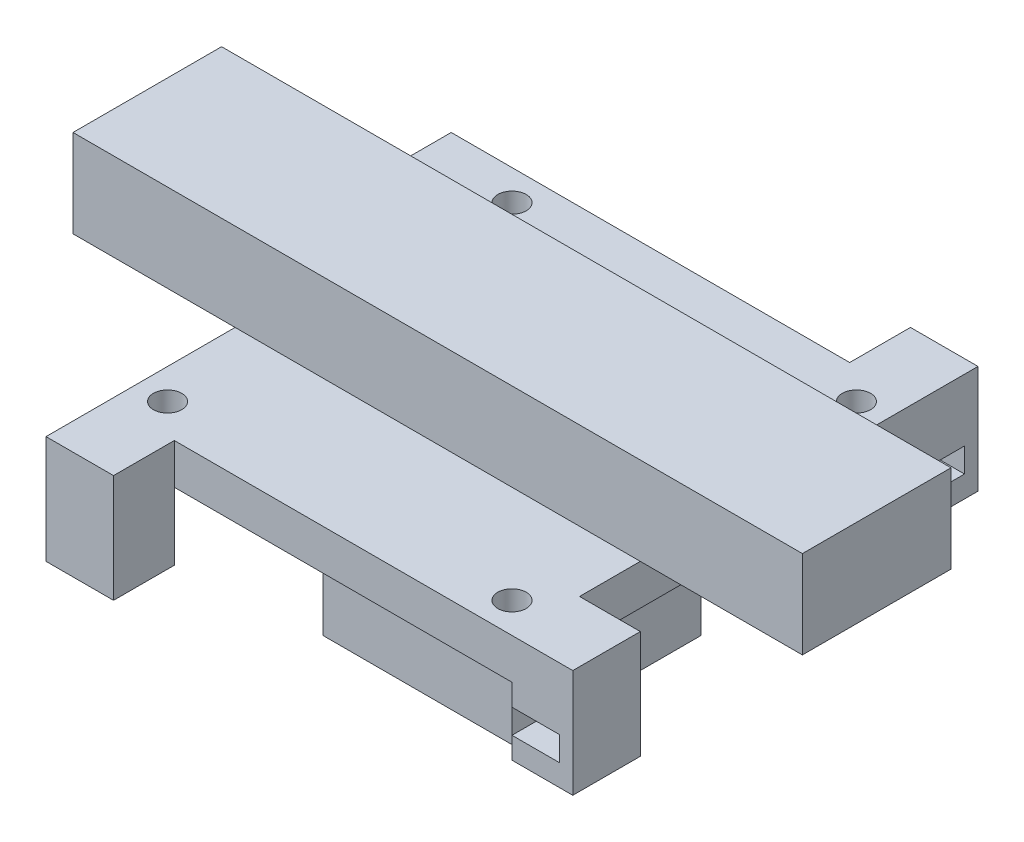
SolidWorks part; units mm, degrees
ref_plane "Front Plane" through (0, 0, 0) normal (0, 0, 1) x (1, 0, 0)
ref_plane "Top Plane" through (0, 0, 0) normal (0, 1, 0) x (1, 0, 0)
ref_plane "Right Plane" through (0, 0, 0) normal (1, 0, 0) x (0, 0, -1)
sketch "Sketch1" plane through (0, 0, 0) normal (0, 1, 0) x (1, 0, 0)
  line L0 (15, -10) -> (19.5, -10)
  line L1 (-15, 15) -> (15, 15)
  line L2 (-15, 15) -> (-15, -15)
  line L3 (-15, -15) -> (15, -15)
  line L4 (15, 15) -> (15, -15)
  line L29 (-15, -15) -> (-10, -15)
  line L30 (-15, -15) -> (-15, -19.5)
  line L35 (-15, -19.5) -> (-10, -19.5)
  line L36 (-10, -15) -> (-10, -19.5)
  line L37 (-19.5, 15) -> (-15, 15)
  line L38 (-19.5, 15) -> (-19.5, 10)
  line L39 (-19.5, 10) -> (-15, 10)
  line L40 (-15, 15) -> (-15, 10)
  line L41 (15, -10) -> (15, -15)
  line L42 (15, -15) -> (19.5, -15)
  line L43 (19.5, -10) -> (19.5, -15)
  line L44 (10, 19.5) -> (15, 19.5)
  line L45 (10, 19.5) -> (10, 15)
  line L46 (10, 15) -> (15, 15)
  line L47 (15, 19.5) -> (15, 15)
  line L48 (-15, 10) -> (-9.3723, 10) construction
  dimension "D5" = 5
  dimension "D1" = 4.5
  dimension "D2" = 5
  dimension "D3" = 5
  dimension "D4" = 4.5
  dimension "D6" = 4.5
  dimension "D7" = 4.5
  dimension "D8" = 5
extrude "Boss-Extrude1" add sketch "Sketch1" along normal blind 3 contours L38 L39 L2 L37 | L47 L44 L45 L1 | L43 L0 L4 L42 | L36 L3 L30 L35
sketch "Sketch8" plane through (0, 0, 0) normal (0, -1, 0) x (-1, 0, 0)
  line L5 (-12.75, -12.75) -> (12.75, -12.75) construction
  line L6 (-12.75, -12.75) -> (-12.75, 12.75) construction
  line L7 (-12.75, 12.75) -> (12.75, 12.75) construction
  line L8 (12.75, -12.75) -> (12.75, 12.75) construction
  line L9 (-12.75, -12.75) -> (12.75, 12.75) construction
  line L10 (-12.75, 12.75) -> (12.75, -12.75) construction
  circle A0 centre (-12.75, 12.75) radius 1.05
  circle A1 centre (12.75, 12.75) radius 1.05
  circle A2 centre (12.75, -12.75) radius 1.05
  circle A3 centre (-12.75, -12.75) radius 1.05
  point P0 (0, 0)
  dimension "D3" = 2.1
  dimension "D1" = 25.5
  dimension "D2" = 25.5
sketch "Sketch9" plane through (0, 0, 0) normal (0, -1, 0) x (-1, 0, 0)
  circle A0 centre (0, 0) radius 7.5
  dimension "D1" = 15
extrude "Cut-Extrude1" cut sketch "Sketch8" against normal through all
extrude "Cut-Extrude2" cut sketch "Sketch9" against normal blind 2
sketch "Sketch10" plane through (0, 0, 0) normal (0, -1, 0) x (1, 0, 0)
  line L0 (-10, 15) -> (-15, 15)
  line L1 (-15, -10) -> (-15, -15)
  line L2 (10, -15) -> (15, -15)
  line L3 (15, 10) -> (15, 15)
  line L12 (-19.5, -10) -> (-19.5, -15)
  line L13 (-19.5, -15) -> (10, -15)
  line L14 (10, -15) -> (10, -19.5)
  line L15 (10, -19.5) -> (15, -19.5)
  line L16 (15, -19.5) -> (15, 10)
  line L17 (15, 10) -> (19.5, 10)
  line L18 (19.5, 10) -> (19.5, 15)
  line L19 (19.5, 15) -> (-10, 15)
  line L20 (-10, 15) -> (-10, 19.5)
  line L21 (-10, 19.5) -> (-15, 19.5)
  line L22 (-15, 19.5) -> (-15, -10)
  line L23 (-15, -10) -> (-19.5, -10)
  line L24 (-19.5, -10) -> (-19.5, -15)
  line L25 (-19.5, -15) -> (10, -15)
  line L26 (10, -15) -> (10, -19.5)
  line L27 (10, -19.5) -> (15, -19.5)
  line L28 (15, -19.5) -> (15, 10)
  line L29 (15, 10) -> (19.5, 10)
  line L30 (19.5, 10) -> (19.5, 15)
  line L31 (19.5, 15) -> (-10, 15)
  line L32 (-10, 15) -> (-10, 19.5)
  line L33 (-10, 19.5) -> (-15, 19.5)
  line L34 (-15, 19.5) -> (-15, -10)
  line L35 (-15, -10) -> (-19.5, -10)
  line M18 (-19.5, -10) -> (-19.5, -15)
  line M19 (-19.5, -15) -> (10, -15)
  line M20 (10, -15) -> (10, -19.5)
  line M21 (10, -19.5) -> (15, -19.5)
  line M22 (15, -19.5) -> (15, 10)
  line M23 (15, 10) -> (19.5, 10)
  line M24 (19.5, 10) -> (19.5, 15)
  line M25 (19.5, 15) -> (-10, 15)
  line M26 (-10, 15) -> (-10, 19.5)
  line M27 (-10, 19.5) -> (-15, 19.5)
  line M28 (-15, 19.5) -> (-15, -10)
  line M29 (-15, -10) -> (-19.5, -10)
  dimension "D1" = 0
extrude "Boss-Extrude2" add sketch "Sketch10" along normal blind 5 contours L0 M26 M27 M28 | L1 M29 M18 M19 | L2 M20 M21 M22 | L3 M23 M24 M25
sketch "Sketch11" plane through (0, -5, 0) normal (0, -1, 0) x (1, 0, 0)
  line L0 (-15, 19.5) -> (-10, 15) construction
  line L1 (-10, 19.5) -> (-15, 19.5) construction
  line L2 (-15, 15) -> (-10, 19.5) construction
  circle A0 centre (-12.5, 17.25) radius 0.6
  dimension "D1" = 1.2
extrude "Cut-Extrude3" cut sketch "Sketch11" against normal blind 6
sketch "Sketch13" plane through (0, 0, 15) normal (0, 0, -1) x (-1, 0, 0)
  line L0 (10, 0) -> (15, -5) construction
  line L1 (10, -5) -> (15, 0) construction
  line L3 (10.85, -3.4) -> (14.15, -3.4)
  line L5 (10.85, -1.6) -> (14.15, -1.6)
  line L7 (10.85, -3.4) -> (14.15, -1.6) construction
  line L8 (10.85, -1.6) -> (14.15, -3.4) construction
  line L12 (10.85, -1.6) -> (10.85, -3.4)
  line L13 (14.15, -1.6) -> (15, -1.6)
  line L14 (15, -5) -> (15, 0) construction
  line L15 (15, -1.6) -> (15, -3.4)
  line L16 (15, -3.4) -> (14.15, -3.4)
  point P8 (12.5, -2.5)
  dimension "D1" = 3.3
  dimension "D2" = 1.8
extrude "Cut-Extrude4" cut sketch "Sketch13" against normal blind 3.5
pattern_circular "CirPattern1" count 4 over 360 about axis through (0, 0, 0) along (0, 1, 0) of "Cut-Extrude4", "Cut-Extrude3"
sketch "Sketch15" plane through (0, 0, 15) normal (0, 0, 1) x (1, 0, 0)
  line L0 (15, -1.6) -> (18.5, -1.6)
  line L1 (18.5, -3.4) -> (18.5, -1.6) construction
  line L2 (18.5, -1.6) -> (15, -1.6) construction
  line L3 (18.5, -1.6) -> (18.5, -3.4)
  line L4 (18.5, -3.4) -> (15, -3.4)
  line L5 (15, -3.4) -> (15, -1.6)
extrude "Cut-Extrude5" cut sketch "Sketch15" against normal blind 4.2
pattern_circular "CirPattern2" count 4 over 360 about axis through (0, 0, 0) along (0, 1, 0) of "Cut-Extrude5"
sketch "Sketch16" plane through (0, 0, 0) normal (0, -1, 0) x (1, 0, 0)
  line L1 (-7.25, -7.25) -> (7.25, -7.25)
  line L2 (-7.25, -7.25) -> (-7.25, 7.25)
  line L3 (-7.25, 7.25) -> (7.25, 7.25)
  line L4 (7.25, -7.25) -> (7.25, 7.25)
  line L5 (-7.25, -7.25) -> (7.25, 7.25) construction
  line L6 (-7.25, 7.25) -> (7.25, -7.25) construction
  point P1 (0, 0)
  dimension "D1" = 14.5
  dimension "D2" = 14.5
extrude "Cut-Extrude6" cut sketch "Sketch16" against normal blind 2
fillet "Fillet1" radius 0.4 4 edges at (7.25, 1, -7.25) (-7.25, 1, -7.25) (7.25, 1, 7.25) (-7.25, 1, 7.25)
sketch "Sketch17" plane through (0, 2, 0) normal (0, -1, 0) x (1, 0, 0)
  line L1 (-7, -7) -> (7, -7)
  line L2 (-7, -7) -> (-7, 7)
  line L3 (-7, 7) -> (7, 7)
  line L4 (7, -7) -> (7, 7)
  line L5 (-7, -7) -> (7, 7) construction
  line L6 (-7, 7) -> (7, -7) construction
  point P0 (0, 0)
  dimension "D1" = 14
  dimension "D2" = 14
extrude "Boss-Extrude3" add sketch "Sketch17" along normal blind 14
sketch "Sketch18" plane through (0, 3, 0) normal (0, 1, 0) x (1, 0, 0)
  line L1 (-27, -5.5) -> (27, -5.5)
  line L2 (-27, -5.5) -> (-27, 5.5)
  line L3 (-27, 5.5) -> (27, 5.5)
  line L4 (27, -5.5) -> (27, 5.5)
  line L5 (-27, -5.5) -> (27, 5.5) construction
  line L6 (-27, 5.5) -> (27, -5.5) construction
  point P0 (0, 0)
  dimension "D1" = 54
  dimension "D2" = 11
extrude "Boss-Extrude4" add sketch "Sketch18" along normal blind 6.5
